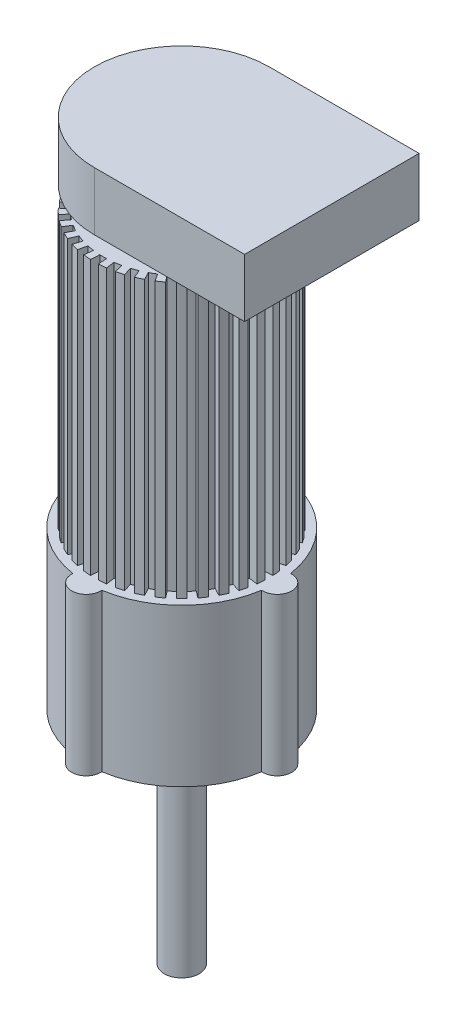
SolidWorks part; units mm, degrees
ref_plane "前视基准面" through (0, 0, 0) normal (0, 0, 1) x (1, 0, 0)
ref_plane "上视基准面" through (0, 0, 0) normal (0, 1, 0) x (1, 0, 0)
ref_plane "右视基准面" through (0, 0, 0) normal (1, 0, 0) x (0, 0, -1)
sketch "草图1" plane through (0, 0, 0) normal (0, 1, 0) x (1, 0, 0)
  circle A0 centre (0, 0) radius 8
  dimension "D1" = 16
extrude "凸台-拉伸1" add sketch "草图1" along normal blind 3
sketch "草图2" plane through (0, 3, 0) normal (0, 1, 0) x (1, 0, 0)
  line L0 (0, 12.8701) -> (0, -12.5799) construction
  line L1 (0, 0) -> (17.876, 0) construction
  circle A0 centre (0, 0) radius 16.4
  circle A1 centre (16.4, 0) radius 2.5
  circle A2 centre (0, 16.4) radius 2.5
  circle A6 centre (0, -16.4) radius 2.5
  circle A7 centre (-16.4, 0) radius 2.5
  point P17 (0, 0)
  point P19 (3.1472, -3.1472)
  dimension "D1" = 32.8
  dimension "D2" = 5
  dimension "D3" = 4
extrude "凸台-拉伸2" add sketch "草图2" along normal blind 27
sketch "草图3" plane through (0, 30, 0) normal (0, 1, 0) x (1, 0, 0)
  circle A0 centre (0, 0) radius 15
  dimension "D1" = 30
extrude "凸台-拉伸4" add sketch "草图3" along normal offset from surface (47 mm away) 74 up to face at (0, 3, 8)
sketch "草图4" plane through (0, 77, 0) normal (0, 1, 0) x (1, 0, 0)
  circle A0 centre (0, 0) radius 11
  dimension "D1" = 22
extrude "凸台-拉伸5" add sketch "草图4" along normal blind 10
sketch "草图7" plane through (0, 0, 0) normal (0, -1, 0) x (1, 0, 0)
  circle A1 centre (0, 0) radius 3
  dimension "D1" = 6
extrude "凸台-拉伸7" add sketch "草图7" along normal blind 34.9
sketch "草图10" plane through (0, 3, 0) normal (0, -1, 0) x (1, 0, 0)
  circle A0 centre (0, 0) radius 11.547 construction
  arc A1 (-2.4927, -16.2095) -> (2.4927, -16.2095) centre (0, -16.4) ccw construction
  circle A2 centre (0, 0) radius 8 construction
  arc A3 (-2.4927, -16.2095) -> (2.4927, -16.2095) centre (0, -16.4) ccw construction
  circle A4 centre (0, 0) radius 8 construction
  circle A5 centre (-2.9886, -11.1536) radius 1.5
  circle A6 centre (-8.165, 8.165) radius 1.5
  circle A7 centre (11.1536, 2.9886) radius 1.5
  point P19 (0, 0)
  dimension "D1" = 20
  dimension "D3" = 3
  dimension "D2" = 3
extrude "切除-拉伸3" cut sketch "草图10" against normal blind 15
sketch "草图13" plane through (0, 0, 0) normal (0, -1, 0) x (1, 0, 0)
  circle A0 centre (0, 0) radius 6.5
  circle A1 centre (0, 0) radius 3
  dimension "D1" = 13
extrude "凸台-拉伸9" add sketch "草图13" along normal blind 0.9
sketch "草图16" plane through (0, 87, 0) normal (0, 1, 0) x (1, 0, 0)
  circle A0 centre (0, 0) radius 11
extrude "凸台-拉伸10" add sketch "草图16" along normal blind 4
sketch "草图17" plane through (0, 91, 0) normal (0, 1, 0) x (1, 0, 0)
  circle A1 centre (0, 0) radius 15
extrude "凸台-拉伸11" add sketch "草图17" against normal blind 5
sketch "草图18" plane through (0, 86, 0) normal (0, -1, 0) x (1, 0, 0)
  line L0 (0, 0) -> (25.8, 0)
  line L1 (25.8, 0) -> (25.8, 14.75)
  line L2 (25.8, 0) -> (25.8, -14.75)
  line L3 (25.8, -14.75) -> (7.1692, -14.75)
  line L4 (7.1692, -14.75) -> (7.1692, 14.75)
  line L5 (7.1692, 14.75) -> (25.8, 14.75)
  arc A0 (2.4927, -16.2095) -> (16.2095, -2.4927) centre (0, 0) ccw construction
  arc A1 (16.2095, 2.4927) -> (2.4927, 16.2095) centre (0, 0) ccw construction
  circle M1 centre (0, 0) radius 11
  circle M2 centre (0, 0) radius 15
extrude "凸台-拉伸12" add sketch "草图18" against normal up to surface (5 mm away) contours L5 L4 L0 L1 M2 | L4 L3 L2 L0 M2 | L4 L0 M2 M1 | L4 L0 M1 M2
sketch "草图19" plane through (0, 91, 0) normal (0, 1, 0) x (1, 0, 0)
  line L0 (0, 15) -> (25.764, 15)
  line L1 (25.764, 15) -> (25.8, 14.75)
  line L2 (25.8, 14.75) -> (7.1692, 14.75)
  line L3 (7.1692, 14.75) -> (7.1692, 13.1758)
  line L4 (7.1692, 14.75) -> (7.1692, 13.1758) construction
  line L5 (0, -15) -> (25.8, -15)
  line L6 (25.8, -15) -> (25.8, -14.75)
  line L7 (25.8, -14.75) -> (7.1692, -14.75)
  line L8 (7.1692, -14.75) -> (25.8, -14.75) construction
  line L9 (7.1692, -14.75) -> (7.1692, -13.1758)
  line L10 (7.1692, -13.1758) -> (7.1692, -14.75) construction
  arc A0 (0, -15) -> (7.1692, -13.1758) centre (0, 0) ccw
  arc A1 (2.4927, -16.2095) -> (16.2095, -2.4927) centre (0, 0) ccw construction
  arc A2 (7.1692, 13.1758) -> (0, 15) centre (0, 0) ccw
extrude "凸台-拉伸13" add sketch "草图19" against normal up to vertex
sketch "草图20" plane through (0, 91, 0) normal (0, 1, 0) x (1, 0, 0)
  line L0 (0, 15) -> (25.764, 15)
  line L1 (25.764, 15) -> (0, 15) construction
  line L2 (25.764, 15) -> (25.8, -15)
  line L3 (25.8, -15) -> (0, -15)
  arc A0 (0, 15) -> (0, -15) centre (0, 0) ccw
extrude "凸台-拉伸14" add sketch "草图20" against normal blind 10
sketch "草图22" plane through (0, 91, 0) normal (0, 1, 0) x (1, 0, 0)
  line L0 (25.764, 15) -> (25.8, -15)
  line L1 (25.8, -15) -> (19.341, -15)
  line L2 (0, -15) -> (25.8, -15) construction
  line L3 (19.341, -15) -> (19.341, 15)
  line L4 (25.764, 15) -> (0, 15) construction
  line L5 (19.341, 15) -> (25.764, 15)
extrude "凸台-拉伸15" add sketch "草图22" against normal blind 10
sketch "草图24" plane through (0, 81, 0) normal (0, -1, 0) x (1, 0, 0)
  line L0 (25.8, 15) -> (25.764, -15)
  line L1 (25.764, -15) -> (34.7082, -13.4442)
  line L2 (34.7082, -13.4442) -> (25.8, 15)
extrude "切除-拉伸4" cut sketch "草图24" against normal blind 10
sketch "草图25" plane through (0, 30, 0) normal (0, 1, 0) x (1, 0, 0)
  line L0 (-0.5889, -13.4872) -> (-0.6543, -14.9857)
  line L3 (0.5889, -13.4872) -> (0.6543, -14.9857)
  line L4 (-2.9219, -13.18) -> (-3.2466, -14.6444)
  line L5 (-1.7621, -13.3845) -> (-1.9579, -14.8717)
  line L6 (-5.1662, -12.4724) -> (-5.7403, -13.8582)
  line L7 (-4.0595, -12.8752) -> (-4.5106, -14.3058)
  line L8 (-7.2535, -11.3858) -> (-8.0595, -12.6509)
  line L9 (-6.2336, -11.9746) -> (-6.9262, -13.3052)
  line L10 (-9.1205, -9.9532) -> (-10.1339, -11.0592)
  line L11 (-8.2183, -10.7103) -> (-9.1314, -11.9003)
  line L12 (-10.7103, -8.2183) -> (-11.9003, -9.1314)
  line L13 (-9.9532, -9.1205) -> (-11.0592, -10.1339)
  line L14 (-11.9746, -6.2336) -> (-13.3052, -6.9262)
  line L15 (-11.3858, -7.2535) -> (-12.6509, -8.0595)
  line L16 (-12.8752, -4.0595) -> (-14.3058, -4.5106)
  line L17 (-12.4724, -5.1662) -> (-13.8582, -5.7403)
  line L18 (-13.3845, -1.7621) -> (-14.8717, -1.9579)
  line L19 (-13.18, -2.9219) -> (-14.6444, -3.2466)
  line L20 (-13.4872, 0.5889) -> (-14.9857, 0.6543)
  line L21 (-13.4872, -0.5889) -> (-14.9857, -0.6543)
  line L22 (-13.18, 2.9219) -> (-14.6444, 3.2466)
  line L23 (-13.3845, 1.7621) -> (-14.8717, 1.9579)
  line L24 (-12.4724, 5.1662) -> (-13.8582, 5.7403)
  line L25 (-12.8752, 4.0595) -> (-14.3058, 4.5106)
  line L26 (-11.3858, 7.2535) -> (-12.6509, 8.0595)
  line L27 (-11.9746, 6.2336) -> (-13.3052, 6.9262)
  line L28 (-9.9532, 9.1205) -> (-11.0592, 10.1339)
  line L29 (-10.7103, 8.2183) -> (-11.9003, 9.1314)
  line L30 (-8.2183, 10.7103) -> (-9.1314, 11.9003)
  line L31 (-9.1205, 9.9532) -> (-10.1339, 11.0592)
  line L32 (-6.2336, 11.9746) -> (-6.9262, 13.3052)
  line L33 (-7.2535, 11.3858) -> (-8.0595, 12.6509)
  line L34 (-4.0595, 12.8752) -> (-4.5106, 14.3058)
  line L35 (-5.1662, 12.4724) -> (-5.7403, 13.8582)
  line L36 (-1.7621, 13.3845) -> (-1.9579, 14.8717)
  line L37 (-2.9219, 13.18) -> (-3.2466, 14.6444)
  line L38 (0.5889, 13.4872) -> (0.6543, 14.9857)
  line L39 (-0.5889, 13.4872) -> (-0.6543, 14.9857)
  line L40 (2.9219, 13.18) -> (3.2466, 14.6444)
  line L41 (1.7621, 13.3845) -> (1.9579, 14.8717)
  line L42 (5.1662, 12.4724) -> (5.7403, 13.8582)
  line L43 (4.0595, 12.8752) -> (4.5106, 14.3058)
  line L44 (7.2535, 11.3858) -> (8.0595, 12.6509)
  line L45 (6.2336, 11.9746) -> (6.9262, 13.3052)
  line L46 (9.1205, 9.9532) -> (10.1339, 11.0592)
  line L47 (8.2183, 10.7103) -> (9.1314, 11.9003)
  line L48 (10.7103, 8.2183) -> (11.9003, 9.1314)
  line L49 (9.9532, 9.1205) -> (11.0592, 10.1339)
  line L50 (11.9746, 6.2336) -> (13.3052, 6.9262)
  line L51 (11.3858, 7.2535) -> (12.6509, 8.0595)
  line L52 (12.8752, 4.0595) -> (14.3058, 4.5106)
  line L53 (12.4724, 5.1662) -> (13.8582, 5.7403)
  line L54 (13.3845, 1.7621) -> (14.8717, 1.9579)
  line L55 (13.18, 2.9219) -> (14.6444, 3.2466)
  line L56 (13.4872, -0.5889) -> (14.9857, -0.6543)
  line L57 (13.4872, 0.5889) -> (14.9857, 0.6543)
  line L58 (13.18, -2.9219) -> (14.6444, -3.2466)
  line L59 (13.3845, -1.7621) -> (14.8717, -1.9579)
  line L60 (12.4724, -5.1662) -> (13.8582, -5.7403)
  line L61 (12.8752, -4.0595) -> (14.3058, -4.5106)
  line L62 (11.3858, -7.2535) -> (12.6509, -8.0595)
  line L63 (11.9746, -6.2336) -> (13.3052, -6.9262)
  line L64 (9.9532, -9.1205) -> (11.0592, -10.1339)
  line L65 (10.7103, -8.2183) -> (11.9003, -9.1314)
  line L66 (8.2183, -10.7103) -> (9.1314, -11.9003)
  line L67 (9.1205, -9.9532) -> (10.1339, -11.0592)
  line L68 (6.2336, -11.9746) -> (6.9262, -13.3052)
  line L69 (7.2535, -11.3858) -> (8.0595, -12.6509)
  line L70 (4.0595, -12.8752) -> (4.5106, -14.3058)
  line L71 (5.1662, -12.4724) -> (5.7403, -13.8582)
  line L187 (2.9219, -13.18) -> (3.2466, -14.6444)
  line L188 (2.3443, -13.2949) -> (2.6047, -14.7721)
  line L189 (1.7621, -13.3845) -> (1.9579, -14.8717)
  arc A1 (1.7621, -13.3845) -> (2.9219, -13.18) centre (0, 0) ccw
  arc A2 (1.9579, -14.8717) -> (3.2466, -14.6444) centre (0, 0) ccw
  arc A3 (-0.6543, -14.9857) -> (0.6543, -14.9857) centre (0, 0) ccw
  arc A4 (-0.5889, -13.4872) -> (0.5889, -13.4872) centre (0, 0) ccw
  arc A5 (-3.2466, -14.6444) -> (-1.9579, -14.8717) centre (0, 0) ccw
  arc A6 (-2.9219, -13.18) -> (-1.7621, -13.3845) centre (0, 0) ccw
  arc A7 (-5.7403, -13.8582) -> (-4.5106, -14.3058) centre (0, 0) ccw
  arc A8 (-5.1662, -12.4724) -> (-4.0595, -12.8752) centre (0, 0) ccw
  arc A9 (-8.0595, -12.6509) -> (-6.9262, -13.3052) centre (0, 0) ccw
  arc A10 (-7.2535, -11.3858) -> (-6.2336, -11.9746) centre (0, 0) ccw
  arc A11 (-10.1339, -11.0592) -> (-9.1314, -11.9003) centre (0, 0) ccw
  arc A12 (-9.1205, -9.9532) -> (-8.2183, -10.7103) centre (0, 0) ccw
  arc A13 (-11.9003, -9.1314) -> (-11.0592, -10.1339) centre (0, 0) ccw
  arc A14 (-10.7103, -8.2183) -> (-9.9532, -9.1205) centre (0, 0) ccw
  arc A15 (-13.3052, -6.9262) -> (-12.6509, -8.0595) centre (0, 0) ccw
  arc A16 (-11.9746, -6.2336) -> (-11.3858, -7.2535) centre (0, 0) ccw
  arc A17 (-14.3058, -4.5106) -> (-13.8582, -5.7403) centre (0, 0) ccw
  arc A18 (-12.8752, -4.0595) -> (-12.4724, -5.1662) centre (0, 0) ccw
  arc A19 (-14.8717, -1.9579) -> (-14.6444, -3.2466) centre (0, 0) ccw
  arc A20 (-13.3845, -1.7621) -> (-13.18, -2.9219) centre (0, 0) ccw
  arc A21 (-14.9857, 0.6543) -> (-14.9857, -0.6543) centre (0, 0) ccw
  arc A22 (-13.4872, 0.5889) -> (-13.4872, -0.5889) centre (0, 0) ccw
  arc A23 (-14.6444, 3.2466) -> (-14.8717, 1.9579) centre (0, 0) ccw
  arc A24 (-13.18, 2.9219) -> (-13.3845, 1.7621) centre (0, 0) ccw
  arc A25 (-13.8582, 5.7403) -> (-14.3058, 4.5106) centre (0, 0) ccw
  arc A26 (-12.4724, 5.1662) -> (-12.8752, 4.0595) centre (0, 0) ccw
  arc A27 (-12.6509, 8.0595) -> (-13.3052, 6.9262) centre (0, 0) ccw
  arc A28 (-11.3858, 7.2535) -> (-11.9746, 6.2336) centre (0, 0) ccw
  arc A29 (-11.0592, 10.1339) -> (-11.9003, 9.1314) centre (0, 0) ccw
  arc A30 (-9.9532, 9.1205) -> (-10.7103, 8.2183) centre (0, 0) ccw
  arc A31 (-9.1314, 11.9003) -> (-10.1339, 11.0592) centre (0, 0) ccw
  arc A32 (-8.2183, 10.7103) -> (-9.1205, 9.9532) centre (0, 0) ccw
  arc A33 (-6.9262, 13.3052) -> (-8.0595, 12.6509) centre (0, 0) ccw
  arc A34 (-6.2336, 11.9746) -> (-7.2535, 11.3858) centre (0, 0) ccw
  arc A35 (-4.5106, 14.3058) -> (-5.7403, 13.8582) centre (0, 0) ccw
  arc A36 (-4.0595, 12.8752) -> (-5.1662, 12.4724) centre (0, 0) ccw
  arc A37 (-1.9579, 14.8717) -> (-3.2466, 14.6444) centre (0, 0) ccw
  arc A38 (-1.7621, 13.3845) -> (-2.9219, 13.18) centre (0, 0) ccw
  arc A39 (0.6543, 14.9857) -> (-0.6543, 14.9857) centre (0, 0) ccw
  arc A40 (0.5889, 13.4872) -> (-0.5889, 13.4872) centre (0, 0) ccw
  arc A41 (3.2466, 14.6444) -> (1.9579, 14.8717) centre (0, 0) ccw
  arc A42 (2.9219, 13.18) -> (1.7621, 13.3845) centre (0, 0) ccw
  arc A43 (5.7403, 13.8582) -> (4.5106, 14.3058) centre (0, 0) ccw
  arc A44 (5.1662, 12.4724) -> (4.0595, 12.8752) centre (0, 0) ccw
  arc A45 (8.0595, 12.6509) -> (6.9262, 13.3052) centre (0, 0) ccw
  arc A46 (7.2535, 11.3858) -> (6.2336, 11.9746) centre (0, 0) ccw
  arc A47 (10.1339, 11.0592) -> (9.1314, 11.9003) centre (0, 0) ccw
  arc A48 (9.1205, 9.9532) -> (8.2183, 10.7103) centre (0, 0) ccw
  arc A49 (11.9003, 9.1314) -> (11.0592, 10.1339) centre (0, 0) ccw
  arc A50 (10.7103, 8.2183) -> (9.9532, 9.1205) centre (0, 0) ccw
  arc A51 (13.3052, 6.9262) -> (12.6509, 8.0595) centre (0, 0) ccw
  arc A52 (11.9746, 6.2336) -> (11.3858, 7.2535) centre (0, 0) ccw
  arc A53 (14.3058, 4.5106) -> (13.8582, 5.7403) centre (0, 0) ccw
  arc A54 (12.8752, 4.0595) -> (12.4724, 5.1662) centre (0, 0) ccw
  arc A55 (14.8717, 1.9579) -> (14.6444, 3.2466) centre (0, 0) ccw
  arc A56 (13.3845, 1.7621) -> (13.18, 2.9219) centre (0, 0) ccw
  arc A57 (14.9857, -0.6543) -> (14.9857, 0.6543) centre (0, 0) ccw
  arc A58 (13.4872, -0.5889) -> (13.4872, 0.5889) centre (0, 0) ccw
  arc A59 (14.6444, -3.2466) -> (14.8717, -1.9579) centre (0, 0) ccw
  arc A60 (13.18, -2.9219) -> (13.3845, -1.7621) centre (0, 0) ccw
  arc A61 (13.8582, -5.7403) -> (14.3058, -4.5106) centre (0, 0) ccw
  arc A62 (12.4724, -5.1662) -> (12.8752, -4.0595) centre (0, 0) ccw
  arc A63 (12.6509, -8.0595) -> (13.3052, -6.9262) centre (0, 0) ccw
  arc A64 (11.3858, -7.2535) -> (11.9746, -6.2336) centre (0, 0) ccw
  arc A65 (11.0592, -10.1339) -> (11.9003, -9.1314) centre (0, 0) ccw
  arc A66 (9.9532, -9.1205) -> (10.7103, -8.2183) centre (0, 0) ccw
  arc A67 (9.1314, -11.9003) -> (10.1339, -11.0592) centre (0, 0) ccw
  arc A68 (8.2183, -10.7103) -> (9.1205, -9.9532) centre (0, 0) ccw
  arc A69 (6.9262, -13.3052) -> (8.0595, -12.6509) centre (0, 0) ccw
  arc A70 (6.2336, -11.9746) -> (7.2535, -11.3858) centre (0, 0) ccw
  arc A71 (4.5106, -14.3058) -> (5.7403, -13.8582) centre (0, 0) ccw
  arc A72 (4.0595, -12.8752) -> (5.1662, -12.4724) centre (0, 0) ccw
  point P80 (0, 0)
  point P192 (0, 0)
  point P345 (0, 0)
  circle M12 centre (0, 0) radius 15
  dimension "D1" = 36
extrude "切除-拉伸5" cut sketch "草图25" along normal up to next (47 mm away) contours A32 L30 L31 M12 | A30 L28 L29 M12 | A28 L26 L27 M12 | A24 L22 L23 M12 | A20 L18 L19 M12 | A18 L16 L17 M12 | A16 L14 L15 M12 | A12 L10 L11 M12 | A4 L0 L3 M12 | A1 L189 L188 M12 | A1 L188 L187 M12 | A72 L70 L71 M12 | A70 L68 L69 M12 | A68 L66 L67 M12 | A66 L64 L65 M12 | A64 L62 L63 M12 | A62 L60 L61 M12 | A60 L58 L59 M12 | A58 L56 L57 M12 | A56 L54 L55 M12 | A54 L52 L53 M12 | A52 L50 L51 M12 | A50 L48 L49 M12 | A48 L46 L47 M12 | A46 L44 L45 M12 | A44 L42 L43 M12 | A34 L32 L33 M12 | A36 L34 L35 M12 | A38 L36 L37 M12 | A40 L38 L39 M12 | L25 A25 L24 A26 | L20 A21 L21 A22 | L13 A13 L12 A14 | L9 A9 L8 A10 | L7 A7 L6 A8 | L5 A5 L4 A6 | L41 A41 L40 A42
